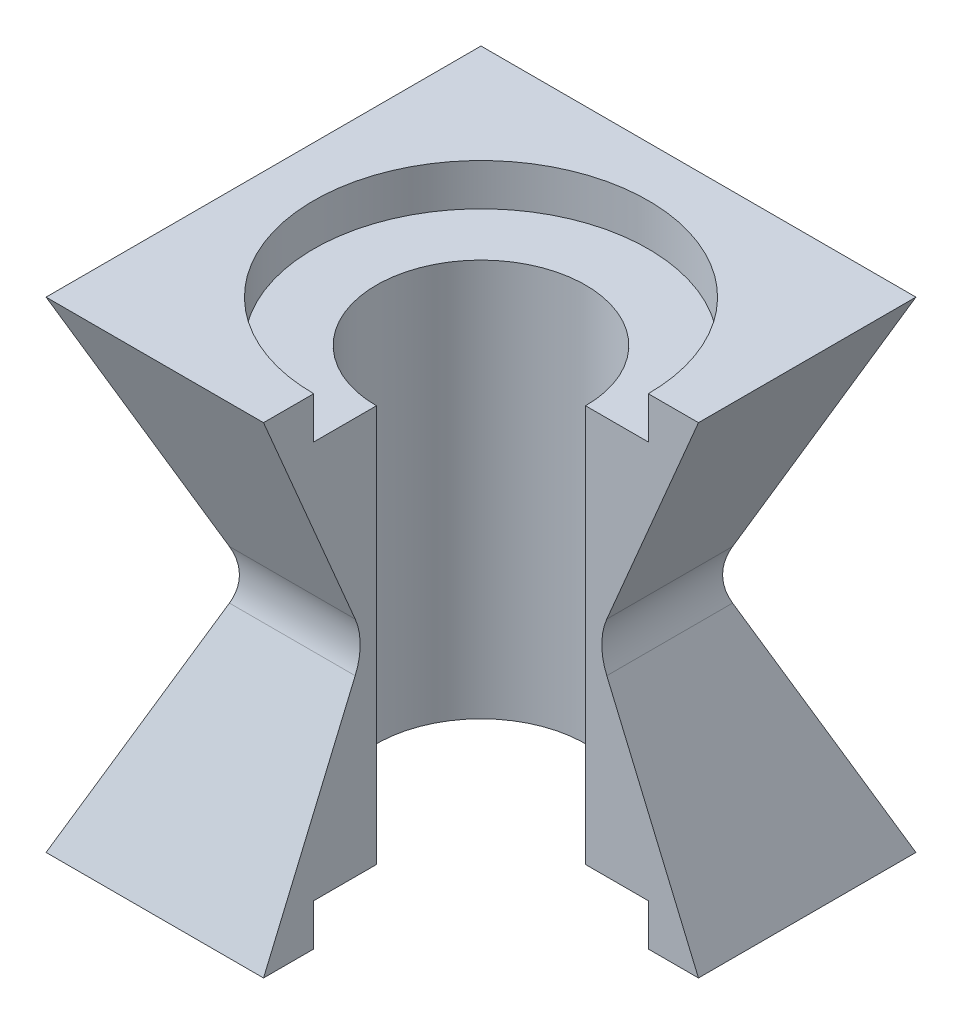
SolidWorks part; units mm, degrees
material "Cast Stainless Steel"
ref_plane "Front Plane" through (0, 0, 0) normal (0, 0, 1) x (1, 0, 0)
ref_plane "Top Plane" through (0, 0, 0) normal (0, 1, 0) x (1, 0, 0)
ref_plane "Right Plane" through (0, 0, 0) normal (1, 0, 0) x (0, 0, -1)
sketch "Sketch2" plane through (0, 0, 0) normal (0, 0, 1) x (1, 0, 0)
  line L1 (0, 0) -> (104, 0)
  line L2 (0, 0) -> (0, 115)
  line L3 (0, 115) -> (104, 115)
  line L4 (104, 0) -> (104, 115)
  dimension "D1" = 115
  dimension "D2" = 104
extrude "Boss-Extrude1" add sketch "Sketch2" along normal blind 104
sketch "Sketch3" plane through (0, 0, 104) normal (0, 0, 1) x (1, 0, 0)
  line L3 (0, 115) -> (24.4073, 57.5)
  line L4 (24.4073, 57.5) -> (0, 0)
  line L5 (0, 0) -> (0, 115)
  line L6 (104, 115) -> (79.5927, 57.5)
  line L7 (79.5927, 57.5) -> (104, 0)
  line L8 (104, 0) -> (104, 115)
  dimension "D1" = 23
  dimension "D2" = 23
extrude "Cut-Extrude1" cut sketch "Sketch3" against normal through all
sketch "Sketch4" plane through (0, 0, 0) normal (1, 0, 0) x (0, 0, -1)
  line L0 (-104, 115) -> (-79.5927, 57.5)
  line L1 (0, 57.5) -> (-104, 57.5) construction
  line L2 (-79.5927, 57.5) -> (-104, 0)
  line L3 (-104, 0) -> (-104, 115)
  line L4 (0, 115) -> (-24.4073, 57.5)
  line L5 (-24.4073, 57.5) -> (0, 0)
  line L6 (0, 0) -> (0, 115)
  dimension "D1" = 23
  dimension "D2" = 23
extrude "Cut-Extrude2" cut sketch "Sketch4" along normal through all
sketch "Sketch5" plane through (0, 115, 0) normal (0, 1, 0) x (1, 0, 0)
  circle A0 centre (52, -52) radius 25
  dimension "D1" = 50
extrude "Cut-Extrude3" cut sketch "Sketch5" against normal through all
sketch "Sketch7" plane through (0, 115, 0) normal (0, 1, 0) x (1, 0, 0)
  circle A2 centre (52, -52) radius 40
  circle A3 centre (52, -52) radius 40
  dimension "D1" = 15
extrude "Cut-Extrude4" cut sketch "Sketch7" against normal blind 10
fillet "Fillet1" radius 15 4 edges at (52, 57.5, 79.5927) (24.4073, 57.5, 52) (52, 57.5, 24.4073) (79.5927, 57.5, 52)
sketch "Sketch8" plane through (0, 115, 0) normal (0, 1, 0) x (1, 0, 0)
  line L0 (52, -104) -> (52, -52) construction
  line L1 (104, -104) -> (0, -104) construction
  line L4 (104, -104) -> (52, -104)
  line L5 (104, -104) -> (104, -52)
  line L6 (104, -52) -> (52, -52)
  line L7 (52, -104) -> (52, -52)
extrude "Cut-Extrude5" cut sketch "Sketch8" against normal through all
sketch "Sketch9" plane through (0, 0, 0) normal (0, -1, 0) x (1, 0, 0)
  arc A2 (52, 92) -> (92, 52) centre (52, 52) ccw
  arc A3 (52, 92) -> (92, 52) centre (52, 52) ccw
  dimension "D1" = 15
extrude "Cut-Extrude6" cut sketch "Sketch9" against normal blind 10 and the other way through all
equation "\"A\"= 115.00"
equation "\"B\"= 104.00"
equation "\"C\"= 23.00"
